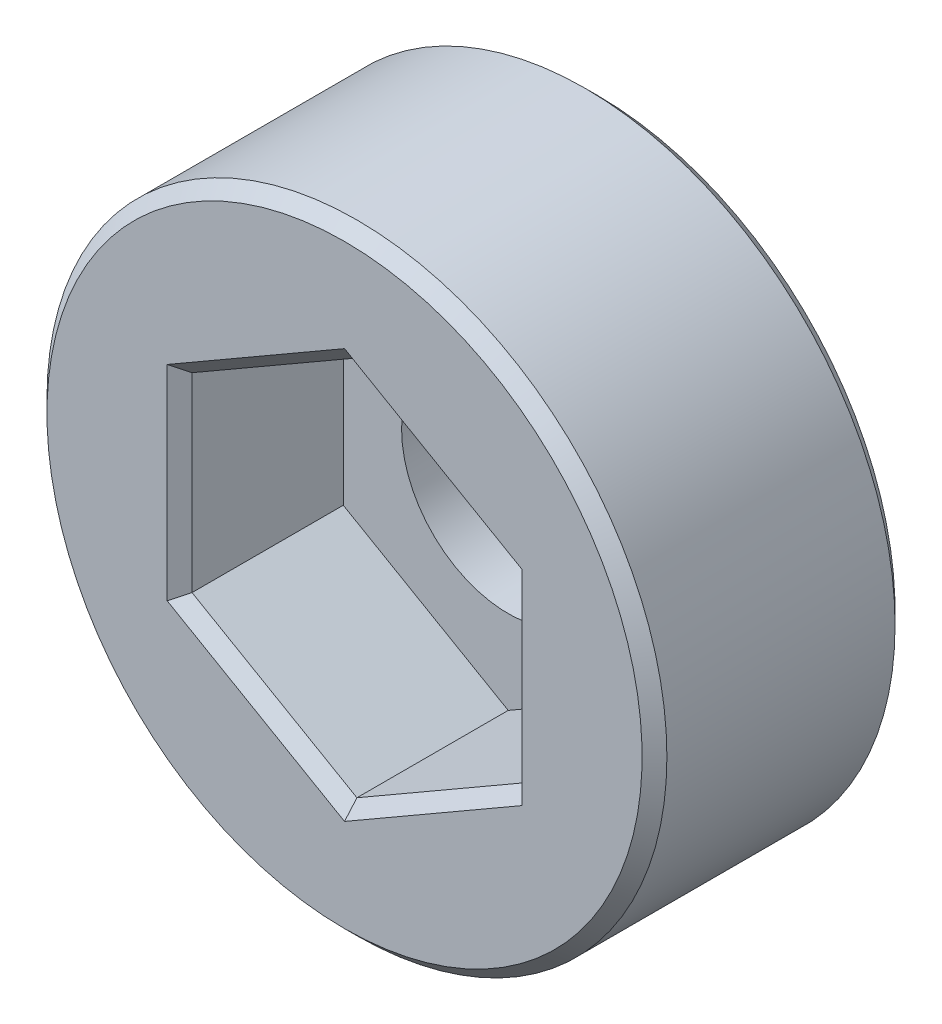
SolidWorks part; units mm, degrees
ref_plane "Front Plane" through (0, 0, 0) normal (0, 0, 1) x (1, 0, 0)
ref_plane "Top Plane" through (0, 0, 0) normal (0, 1, 0) x (1, 0, 0)
ref_plane "Right Plane" through (0, 0, 0) normal (1, 0, 0) x (0, 0, -1)
sketch "Sketch4" plane through (0, 0, 0) normal (1, 0, 0) x (0, 0, -1)
  line L0 (0, 0) -> (-48.7941, 0) construction
  line L1 (0, 12.5) -> (0, 0)
  line L2 (0, 12.5) -> (-10.2, 12.5)
  line L3 (-10.2, 12.5) -> (-10.2, 0)
  line L6 (-10.2, 0) -> (0, 0)
  dimension "D1" = 10.2
  dimension "D2" = 25
revolve "Revolve1" add sketch "Sketch4" angle 360 about L6
sketch "Sketch5" plane through (0, 0, 10.2) normal (0, 0, 1) x (1, 0, 0)
  line L1 (0, -7.6788) -> (6.65, -3.8394)
  line L2 (6.65, -3.8394) -> (6.65, 3.8394)
  line L3 (6.65, 3.8394) -> (0, 7.6788)
  line L4 (0, 7.6788) -> (-6.65, 3.8394)
  line L5 (-6.65, 3.8394) -> (-6.65, -3.8394)
  line L6 (-6.65, -3.8394) -> (0, -7.6788)
  circle A0 centre (0, 0) radius 6.65 construction
  dimension "D1" = 13.3
extrude "Cut-Extrude1" cut sketch "Sketch5" against normal blind 6.6
sketch "Sketch6" plane through (0, 0, 3.6) normal (0, 0, 1) x (1, 0, 0)
  circle A0 centre (0, 0) radius 4.3
  dimension "D1" = 8.6
extrude "Cut-Extrude2" cut sketch "Sketch6" against normal through all
chamfer "Chamfer2" distance 0.5 angle 45 9 edges at (6.65, 0, 10.2) (3.325, -5.7591, 10.2) (-3.325, -5.7591, 10.2) (-6.65, 0, 10.2) (3.325, 5.7591, 10.2) (-3.325, 5.7591, 10.2) (0, -12.5, 0) (4.3, 0, 0) (0, -12.5, 10.2)
